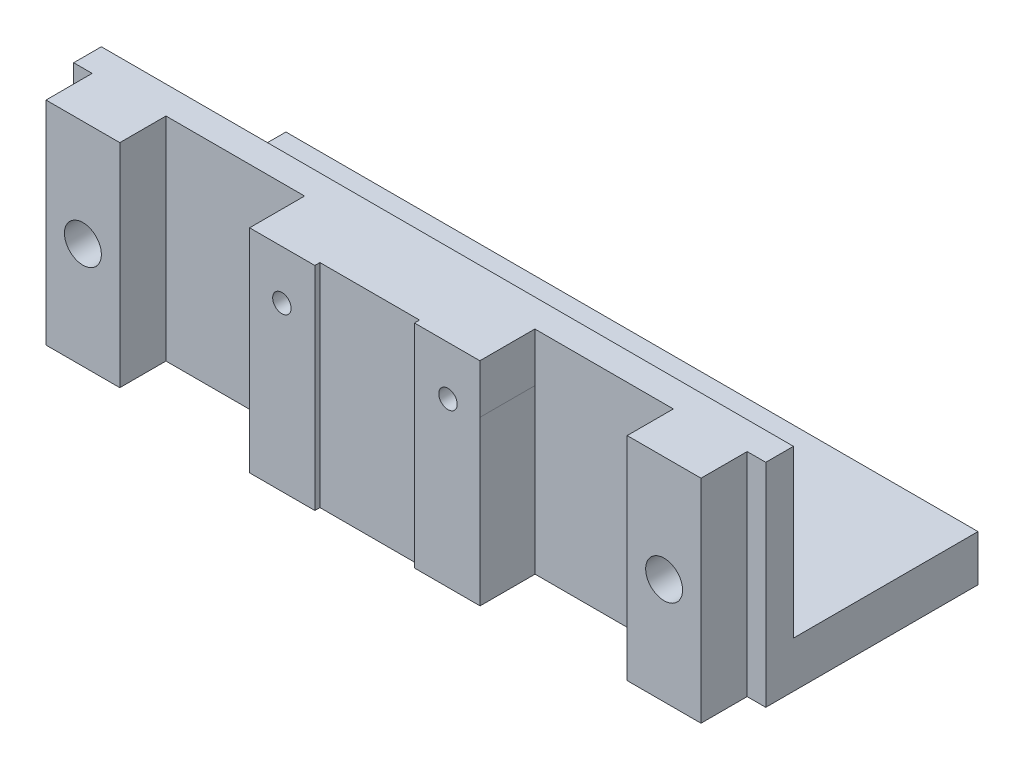
SolidWorks part; units mm, degrees
ref_plane "Front Plane" through (0, 0, 0) normal (0, 0, 1) x (1, 0, 0)
ref_plane "Top Plane" through (0, 0, 0) normal (0, 1, 0) x (1, 0, 0)
ref_plane "Right Plane" through (0, 0, 0) normal (1, 0, 0) x (0, 0, -1)
sketch "Sketch1" plane through (0, 0, 0) normal (0, 1, 0) x (1, 0, 0)
  line L1 (-25, -11.5) -> (25, -11.5)
  line L2 (-25, -11.5) -> (-25, 11.5)
  line L3 (-25, 11.5) -> (25, 11.5)
  line L4 (25, -11.5) -> (25, 11.5)
  line L5 (-25, -11.5) -> (25, 11.5) construction
  line L6 (-25, 11.5) -> (25, -11.5) construction
  point P0 (0, 0)
extrude "Boss-Extrude12" add sketch "Sketch1" along normal blind 3
sketch "Sketch17" plane through (0, 3, 0) normal (0, 1, 0) x (1, 0, 0)
  line L0 (25, -11.5) -> (25, 11.5) construction
  line L1 (-25, -11.5) -> (25, -11.5)
  line L2 (-25, -11.5) -> (-25, -8.5)
  line L3 (-25, -8.5) -> (25, -8.5)
  line L4 (25, -11.5) -> (25, -8.5)
extrude "Boss-Extrude13" add sketch "Sketch17" along normal blind 20
sketch "Sketch18" plane through (25, 0, 0) normal (1, 0, 0) x (0, 0, -1)
  line L0 (-11.5, 23) -> (-8.5, 23)
  line L1 (-8.5, 23) -> (-8.5, 3)
  line L2 (-8.5, 3) -> (11.5, 3)
  line L3 (11.5, 3) -> (11.5, 0)
  line L4 (11.5, 0) -> (-11.5, 0)
  line L5 (-11.5, 0) -> (-11.5, 23)
extrude "Boss-Extrude15" add sketch "Sketch18" along normal blind 25
sketch "Sketch19" plane through (0, 0, 0) normal (0, -1, 0) x (1, 0, 0)
  circle A0 centre (-7.5, -1.0693) radius 3
  circle A1 centre (12.5, -1.0693) radius 3
  circle A2 centre (32.5, -1.0693) radius 3
extrude "Cut-Extrude1" cut sketch "Sketch19" against normal blind 10
sketch "Sketch20" plane through (0, 0, 0) normal (0, -1, 0) x (1, 0, 0)
  circle A3 centre (-7.5, -1.0693) radius 3
  circle A4 centre (12.5, -1.0693) radius 3
  circle A5 centre (32.5, -1.0693) radius 3
  circle A6 centre (-7.5, -1.0693) radius 4
  circle A7 centre (12.5, -1.0693) radius 4
  circle A8 centre (32.5, -1.0693) radius 4
sketch "Sketch21" plane through (0, 0, 11.5) normal (0, 0, 1) x (1, 0, 0)
  line L1 (-25, 23) -> (50, 23) construction
  line L4 (0.0228, 17.6839) -> (0, 0)
  line L5 (0, 0) -> (25, 0)
  line L6 (0.0228, 17.6839) -> (0.0228, 23)
  line L7 (0.0228, 23) -> (24.9772, 23)
  line L8 (24.9772, 17.6839) -> (24.9772, 23)
  line L9 (24.9772, 17.6839) -> (25, 0)
  arc A0 (1.7156, 21.4339) -> (1.7156, 13.9339) centre (5.0228, 17.6839) ccw construction
extrude "Boss-Extrude17" add sketch "Sketch21" along normal blind 5.96
sketch "Sketch22" plane through (0, 23, 0) normal (0, 1, 0) x (1, 0, 0)
  line L0 (15.8929, -16.909) -> (17.8908, -16.909)
  line L1 (17.8908, -16.909) -> (17.8908, -17.46)
  line L2 (24.9772, -17.46) -> (0.0228, -17.46) construction
  line L3 (15.8929, -16.909) -> (9.0929, -16.909)
  line L4 (9.0929, -16.909) -> (7.0929, -16.909)
  line L5 (7.0929, -16.909) -> (7.0929, -17.46)
  line L6 (7.0929, -17.46) -> (17.8908, -17.46)
extrude "Cut-Extrude2" cut sketch "Sketch22" against normal through all
sketch "Sketch23" plane through (0, 0, 17.46) normal (0, 0, 1) x (1, 0, 0)
  circle A0 centre (3.5228, 17.6839) radius 1
  circle A1 centre (21.5228, 17.6839) radius 1
extrude "Cut-Extrude3" cut sketch "Sketch23" against normal through all
sketch "Sketch24" plane through (0, 0, 11.5) normal (0, 0, 1) x (1, 0, 0)
  line L1 (-25, 23) -> (0.0228, 23) construction
  line L2 (-23, 23) -> (-23, 0)
  line L3 (-25, 0) -> (0, 0) construction
  line L4 (-23, 0) -> (-15, 0)
  line L5 (-15, 0) -> (-15, 23)
  line L6 (-15, 23) -> (-23, 23)
  line L13 (39.9837, 23) -> (47.9837, 23)
  line L14 (39.9837, 0) -> (39.9837, 23)
  line L15 (47.9837, 0) -> (39.9837, 0)
  line L16 (47.9837, 23) -> (47.9837, 0)
extrude "Boss-Extrude20" add sketch "Sketch24" along normal blind 5
extrude "Boss-Extrude22" add sketch "Sketch20" along normal blind 3
sketch "Sketch25" plane through (0, 0, 16.5) normal (0, 0, 1) x (1, 0, 0)
  line L3 (12.4929, 23.1217) -> (12.4919, 0)
  line L4 (15.8929, 23.1217) -> (9.0929, 23.1217) construction
  line L5 (17.8908, 0) -> (7.0929, 0) construction
  circle A0 centre (-19, 11.5) radius 2
  circle A1 centre (43.9847, 11.4973) radius 2
extrude "Cut-Extrude4" cut sketch "Sketch25" against normal through all contours A1 | A0
sketch "Sketch26" plane through (0, 3, 0) normal (0, 1, 0) x (1, 0, 0)
  line L1 (-25, 11.5) -> (50, 11.5)
  line L2 (-25, 11.5) -> (-25, -8.5)
  line L3 (-25, -8.5) -> (50, -8.5)
  line L4 (50, 11.5) -> (50, -8.5)
extrude "Boss-Extrude23" add sketch "Sketch26" along normal blind 2
sketch "Sketch27" plane through (0, 3, 0) normal (0, -1, 0) x (1, 0, 0)
  circle A0 centre (-7.5, -1.0693) radius 3
  circle A1 centre (12.5, -1.0693) radius 3
  circle A2 centre (32.5, -1.0693) radius 3
extrude "Cut-Extrude5" cut sketch "Sketch27" against normal through all
